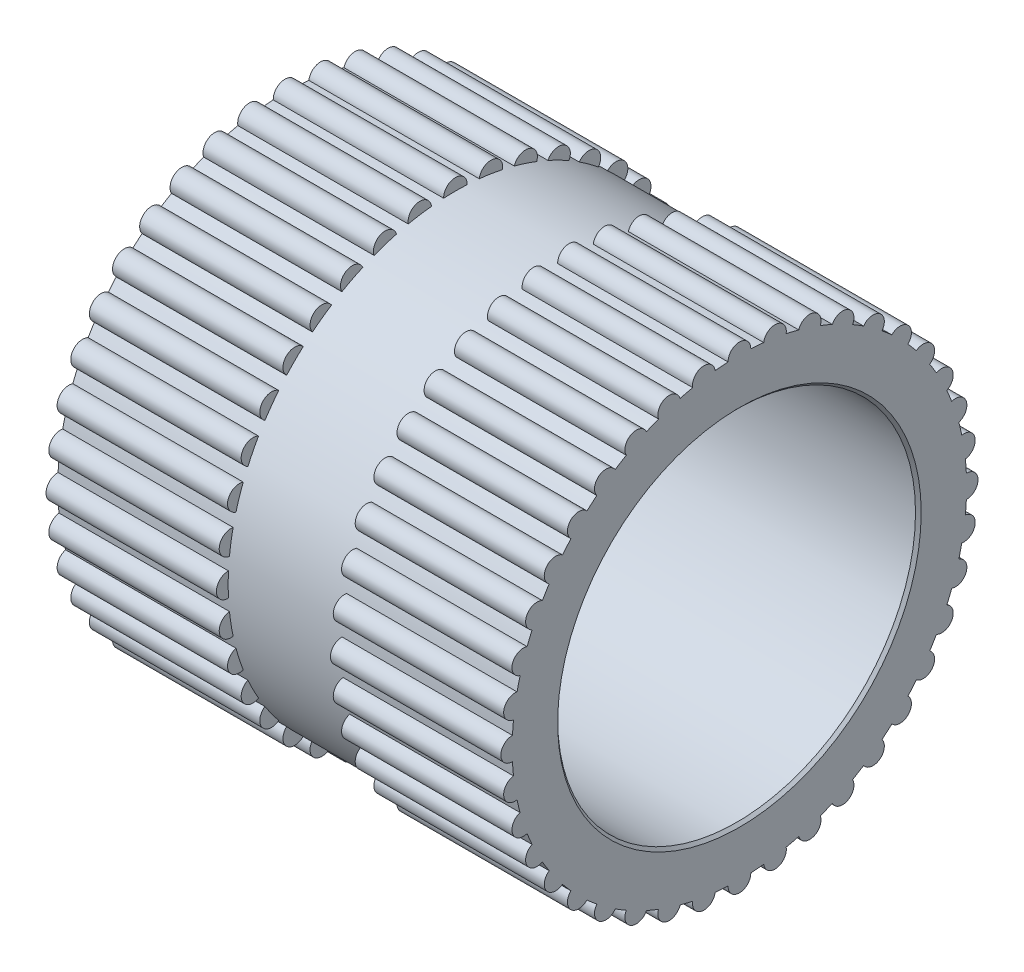
SolidWorks part; units mm, degrees
material "Л63 ГОСТ 15527-70"
ref_plane "Спереди" through (0, 0, 0) normal (0, 0, 1) x (1, 0, 0)
ref_plane "Сверху" through (0, 0, 0) normal (0, 1, 0) x (1, 0, 0)
ref_plane "Справа" through (0, 0, 0) normal (1, 0, 0) x (0, 0, -1)
other "Configuration Table"
sketch "Эскиз1" plane through (0, 0, 0) normal (1, 0, 0) x (0, 0, -1)
  circle A1 centre (0, 0) radius 2
  dimension "D1" = 4
extrude "Бобышка-Вытянуть1" add sketch "Эскиз1" along normal blind 4
hole_wizard "Сверло под метчик  спиральное M31" positions "Эскиз3" profile "Эскиз2" hole size "M3x0.5" standard "DIN" end condition through all
sketch "Эскиз3" plane through (4, 0, 0) normal (1, 0, 0) x (0, 0, -1)
  point P1 (0, 0)
  point P5 (0, 0)
sketch "Эскиз2" plane through (4, 0, 0) normal (0, 1, 0) x (0, 0, -1)
  line L0 (0, 0) -> (0, 4)
  line L1 (0, 4) -> (1.575, 4)
  line L2 (1.575, 4) -> (1.575, 0.025)
  line L3 (1.575, 0.025) -> (1.6, 0)
  line L5 (1.6, 0) -> (0, 0)
  line L6 (-1.575, 0.025) -> (-1.6, 0) construction
  line L11 (0, -6.35) -> (0, 107.95) construction
  dimension "Диаметр сквозного отверстия" = 3.15
  dimension "Глубина сквозного отверстия" = 4
  dimension "Диаметр передней зенковки" = 3.2
  dimension "Угол передней зенковки" = 90
sketch "Эскиз4" plane through (4, 0, 0) normal (1, 0, 0) x (0, 0, -1)
  circle A0 centre (0, 2) radius 0.1
  circle A1 centre (0, 0) radius 2 construction
  circle A2 centre (0.3129, 1.9754) radius 0.1
  circle A3 centre (0.618, 1.9021) radius 0.1
  circle A4 centre (0.908, 1.782) radius 0.1
  circle A5 centre (1.1756, 1.618) radius 0.1
  circle A6 centre (1.4142, 1.4142) radius 0.1
  circle A7 centre (1.618, 1.1756) radius 0.1
  circle A8 centre (1.782, 0.908) radius 0.1
  circle A9 centre (1.9021, 0.618) radius 0.1
  circle A10 centre (1.9754, 0.3129) radius 0.1
  circle A11 centre (2, 0) radius 0.1
  circle A12 centre (1.9754, -0.3129) radius 0.1
  circle A13 centre (1.9021, -0.618) radius 0.1
  circle A14 centre (1.782, -0.908) radius 0.1
  circle A15 centre (1.618, -1.1756) radius 0.1
  circle A16 centre (1.4142, -1.4142) radius 0.1
  circle A17 centre (1.1756, -1.618) radius 0.1
  circle A18 centre (0.908, -1.782) radius 0.1
  circle A19 centre (0.618, -1.9021) radius 0.1
  circle A20 centre (0.3129, -1.9754) radius 0.1
  circle A21 centre (0, -2) radius 0.1
  circle A22 centre (-0.3129, -1.9754) radius 0.1
  circle A23 centre (-0.618, -1.9021) radius 0.1
  circle A24 centre (-0.908, -1.782) radius 0.1
  circle A25 centre (-1.1756, -1.618) radius 0.1
  circle A26 centre (-1.4142, -1.4142) radius 0.1
  circle A27 centre (-1.618, -1.1756) radius 0.1
  circle A28 centre (-1.782, -0.908) radius 0.1
  circle A29 centre (-1.9021, -0.618) radius 0.1
  circle A30 centre (-1.9754, -0.3129) radius 0.1
  circle A31 centre (-2, 0) radius 0.1
  circle A32 centre (-1.9754, 0.3129) radius 0.1
  circle A33 centre (-1.9021, 0.618) radius 0.1
  circle A34 centre (-1.782, 0.908) radius 0.1
  circle A35 centre (-1.618, 1.1756) radius 0.1
  circle A36 centre (-1.4142, 1.4142) radius 0.1
  circle A37 centre (-1.1756, 1.618) radius 0.1
  circle A38 centre (-0.908, 1.782) radius 0.1
  circle A39 centre (-0.618, 1.9021) radius 0.1
  circle A40 centre (-0.3129, 1.9754) radius 0.1
  point P84 (0, 0)
  dimension "D2" = 0.2
  dimension "D1" = 40
extrude "Бобышка-Вытянуть2" add sketch "Эскиз4" against normal blind 1.5
sketch "Эскиз5" plane through (0, 0, 0) normal (-1, 0, 0) x (0, 0, 1)
  circle A0 centre (0, 2) radius 0.1037
  circle A1 centre (0, 0) radius 2 construction
  circle A2 centre (0.3129, 1.9754) radius 0.1037
  circle A3 centre (0.618, 1.9021) radius 0.1037
  circle A4 centre (0.908, 1.782) radius 0.1037
  circle A5 centre (1.1756, 1.618) radius 0.1037
  circle A6 centre (1.4142, 1.4142) radius 0.1037
  circle A7 centre (1.618, 1.1756) radius 0.1037
  circle A8 centre (1.782, 0.908) radius 0.1037
  circle A9 centre (1.9021, 0.618) radius 0.1037
  circle A10 centre (1.9754, 0.3129) radius 0.1037
  circle A11 centre (2, 0) radius 0.1037
  circle A12 centre (1.9754, -0.3129) radius 0.1037
  circle A13 centre (1.9021, -0.618) radius 0.1037
  circle A14 centre (1.782, -0.908) radius 0.1037
  circle A15 centre (1.618, -1.1756) radius 0.1037
  circle A16 centre (1.4142, -1.4142) radius 0.1037
  circle A17 centre (1.1756, -1.618) radius 0.1037
  circle A18 centre (0.908, -1.782) radius 0.1037
  circle A19 centre (0.618, -1.9021) radius 0.1037
  circle A20 centre (0.3129, -1.9754) radius 0.1037
  circle A21 centre (0, -2) radius 0.1037
  circle A22 centre (-0.3129, -1.9754) radius 0.1037
  circle A23 centre (-0.618, -1.9021) radius 0.1037
  circle A24 centre (-0.908, -1.782) radius 0.1037
  circle A25 centre (-1.1756, -1.618) radius 0.1037
  circle A26 centre (-1.4142, -1.4142) radius 0.1037
  circle A27 centre (-1.618, -1.1756) radius 0.1037
  circle A28 centre (-1.782, -0.908) radius 0.1037
  circle A29 centre (-1.9021, -0.618) radius 0.1037
  circle A30 centre (-1.9754, -0.3129) radius 0.1037
  circle A31 centre (-2, 0) radius 0.1037
  circle A32 centre (-1.9754, 0.3129) radius 0.1037
  circle A33 centre (-1.9021, 0.618) radius 0.1037
  circle A34 centre (-1.782, 0.908) radius 0.1037
  circle A35 centre (-1.618, 1.1756) radius 0.1037
  circle A36 centre (-1.4142, 1.4142) radius 0.1037
  circle A37 centre (-1.1756, 1.618) radius 0.1037
  circle A38 centre (-0.908, 1.782) radius 0.1037
  circle A39 centre (-0.618, 1.9021) radius 0.1037
  circle A40 centre (-0.3129, 1.9754) radius 0.1037
  point P85 (0, 0)
  dimension "D1" = 40
extrude "Бобышка-Вытянуть3" add sketch "Эскиз5" against normal blind 1.5
